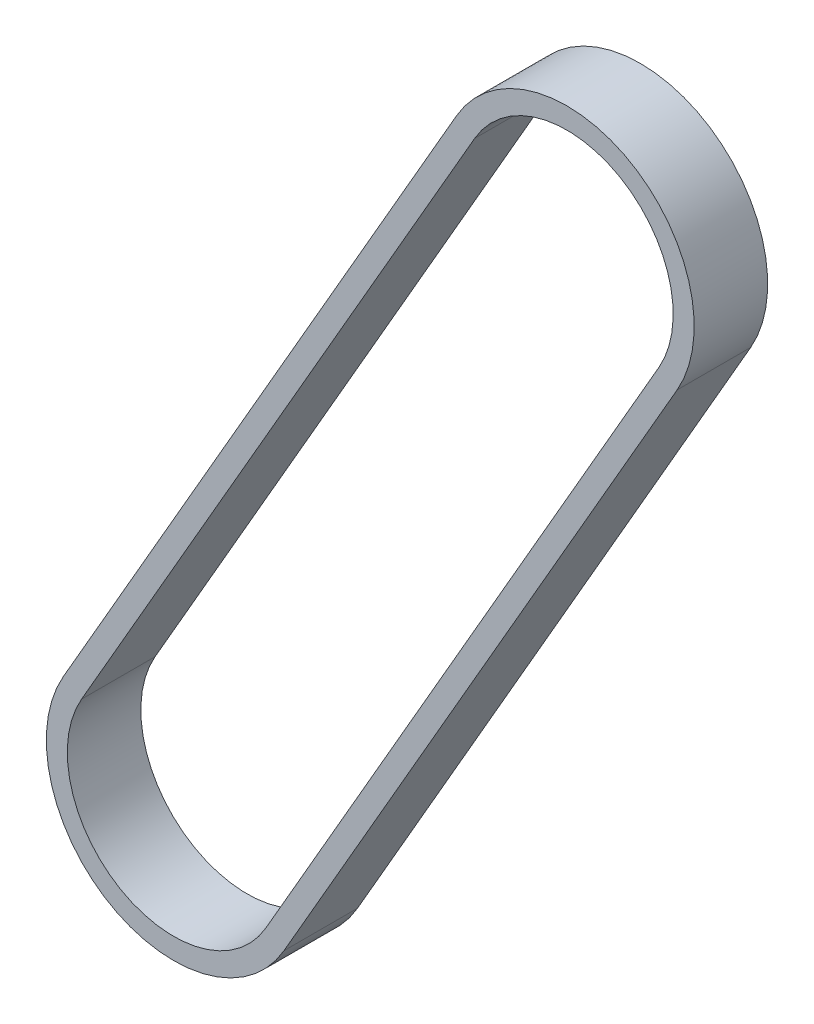
SolidWorks part; units mm, degrees
material "BUTYL"
ref_plane "前视基准面" through (0, 0, 0) normal (0, 0, 1) x (1, 0, 0)
ref_plane "上视基准面" through (0, 0, 0) normal (0, 1, 0) x (1, 0, 0)
ref_plane "右视基准面" through (0, 0, 0) normal (1, 0, 0) x (0, 0, -1)
sketch "草图2" plane through (0, 0, 0) normal (0, 0, 1) x (1, 0, 0)
  line L0 (0, 0) -> (1, 0) construction
  line L1 (0, 0) -> (0, 1) construction
  line L2 (-18.2343, 26.943) -> (-55.6834, -38.0383)
  line L3 (-73.2283, -27.9271) -> (-35.7792, 37.0542)
  arc A0 (-35.7792, 37.0542) -> (-18.2343, 26.943) centre (-27.0067, 31.9986) cw
  arc A1 (-55.6834, -38.0383) -> (-73.2283, -27.9271) centre (-64.4558, -32.9827) cw
extrude "拉伸-薄壁1" add sketch "草图2" along normal mid plane 7 thin thin type one direction wall 2
